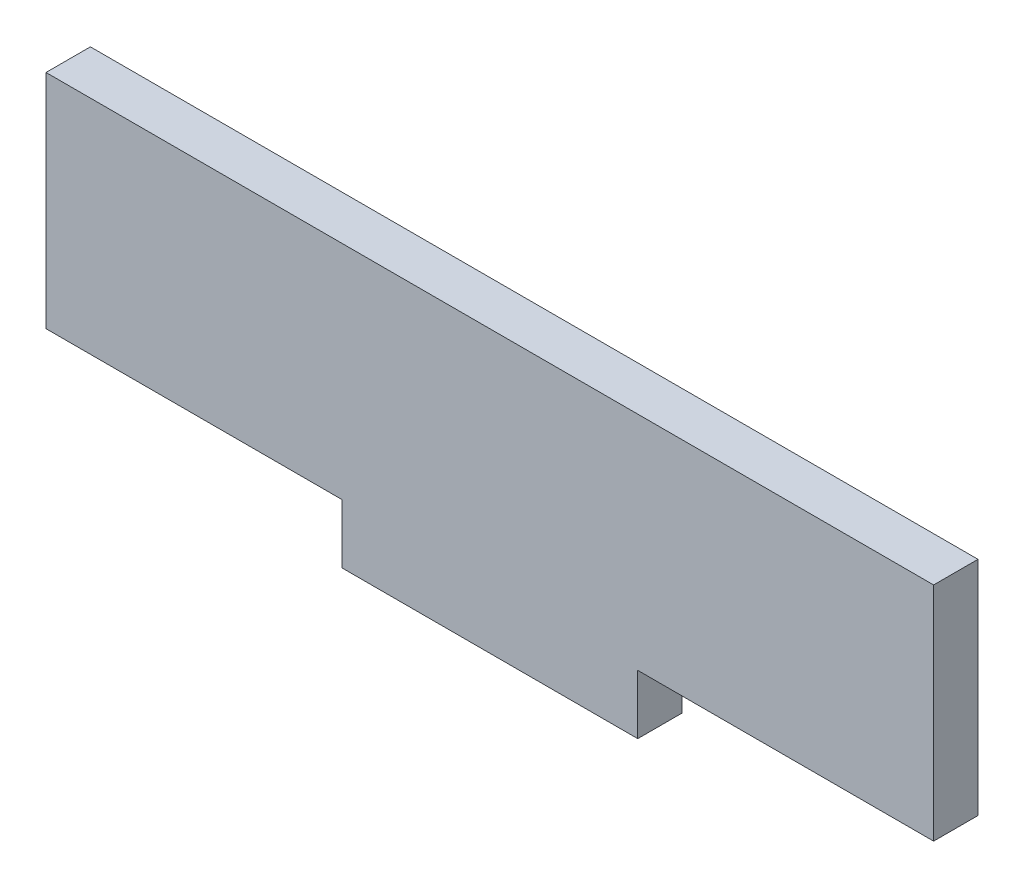
SolidWorks part; units mm, degrees
ref_plane "Front Plane" through (0, 0, 0) normal (0, 0, 1) x (1, 0, 0)
ref_plane "Top Plane" through (0, 0, 0) normal (0, 1, 0) x (1, 0, 0)
ref_plane "Right Plane" through (0, 0, 0) normal (1, 0, 0) x (0, 0, -1)
sketch "Sketch1" plane through (0, 0, 0) normal (0, 0, 1) x (1, 0, 0)
  line L0 (0, 0) -> (0, 15)
  line L1 (0, 15) -> (60, 15)
  line L2 (60, 15) -> (60, 0)
  line L3 (60, 0) -> (40, 0)
  line L4 (40, 0) -> (40, -4)
  line L5 (40, -4) -> (20, -4)
  line L6 (20, -4) -> (20, 0)
  line L7 (20, 0) -> (0, 0)
  dimension "D1" = 60
  dimension "D2" = 20
  dimension "D3" = 15
  dimension "D4" = 4
extrude "Boss-Extrude1" add sketch "Sketch1" along normal blind 3
